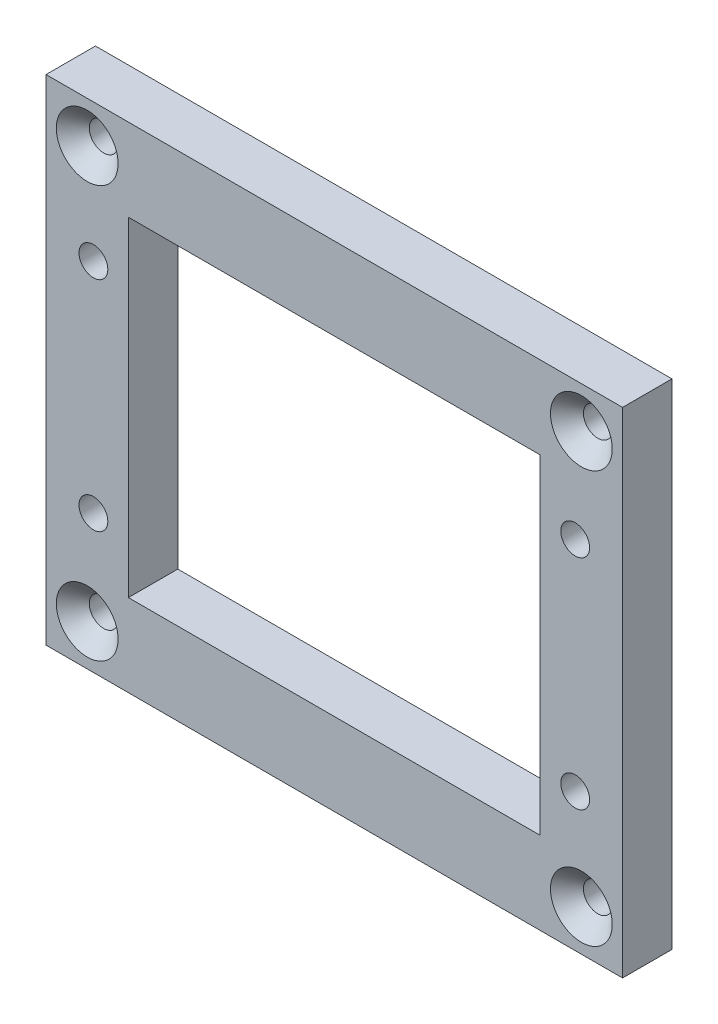
SolidWorks part; units mm, degrees
ref_plane "Front Plane" through (0, 0, 0) normal (0, 0, 1) x (1, 0, 0)
ref_plane "Top Plane" through (0, 0, 0) normal (0, 1, 0) x (1, 0, 0)
ref_plane "Right Plane" through (0, 0, 0) normal (1, 0, 0) x (0, 0, -1)
sketch "Sketch1" plane through (0, 0, 0) normal (0, 0, 1) x (1, 0, 0)
  line L1 (0, 0) -> (70, 0)
  line L2 (0, 0) -> (0, 60)
  line L3 (0, 60) -> (70, 60)
  line L4 (70, 0) -> (70, 60)
  line L5 (10, 50) -> (60, 50)
  line L6 (10, 50) -> (10, 10)
  line L7 (10, 10) -> (60, 10)
  line L8 (60, 50) -> (60, 10)
  circle A0 centre (5.75, 16.75) radius 1.75
  circle A1 centre (5.75, 43.25) radius 1.75
  circle A2 centre (64.25, 43.25) radius 1.75
  circle A3 centre (64.25, 16.75) radius 1.75
  circle A4 centre (5, 55) radius 1.75
  circle A5 centre (65, 55) radius 1.75
  circle A6 centre (65, 5) radius 1.75
  circle A7 centre (5, 5) radius 1.75
  dimension "D1" = 26.5
  dimension "D2" = 58.5
  dimension "D3" = 58.5
  dimension "D5" = 26.5
  dimension "D8" = 3.5
  dimension "D9" = 3.5
  dimension "D10" = 3.5
  dimension "D11" = 3.5
  dimension "D12" = 5.75
  dimension "D13" = 16.75
  dimension "D14" = 16.75
  dimension "D15" = 5
  dimension "D16" = 5
  dimension "D17" = 3.5
  dimension "D4" = 5.75
  dimension "D6" = 60
  dimension "D7" = 70
  dimension "D20" = 10
  dimension "D21" = 10
  dimension "D22" = 10
  dimension "D23" = 10
  dimension "D18" = 2
  dimension "D19" = 2
extrude "Boss-Extrude1" add sketch "Sketch1" along normal blind 6
chamfer "Chamfer1" distance 2 angle 45 4 edges at (6.75, 5, 6) (66.75, 5, 6) (66.75, 55, 6) (6.75, 55, 6)
sketch "Sketch3" plane through (0, 0, 0) normal (0, 0, -1) x (-1, 0, 0)
  circle A0 centre (-64.25, 43.25) radius 3
  circle A1 centre (-64.25, 16.75) radius 3
  circle A2 centre (-5.75, 16.75) radius 3
  circle A3 centre (-5.75, 43.25) radius 3
  dimension "D1" = 6
  dimension "D2" = 6
  dimension "D3" = 6
  dimension "D4" = 6
extrude "Cut-Extrude1" cut sketch "Sketch3" against normal blind 3
